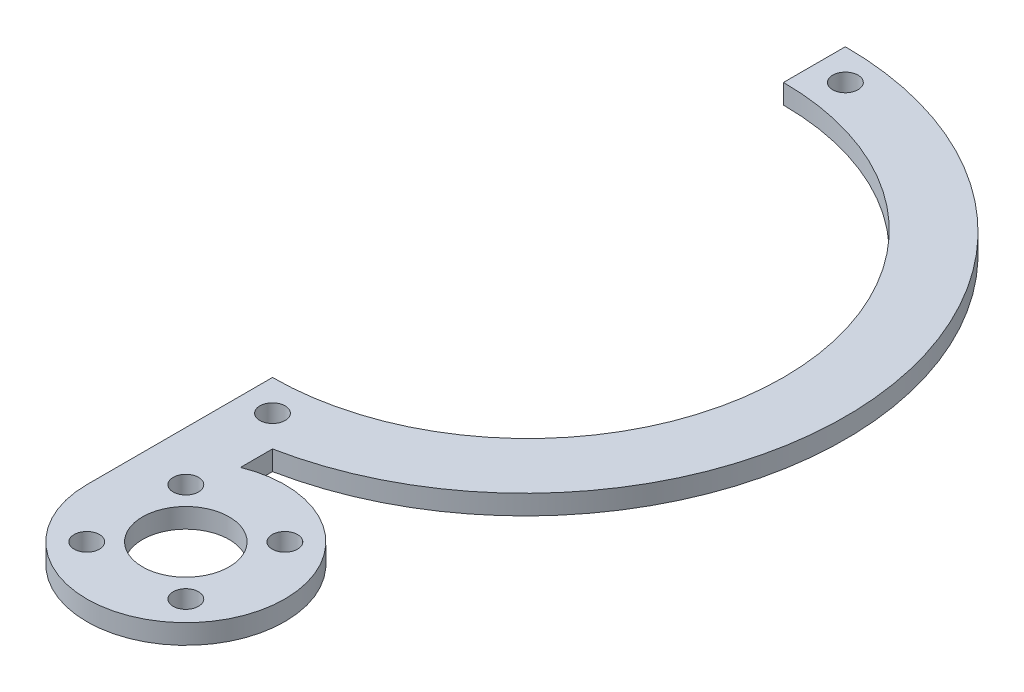
SolidWorks part; units mm, degrees
ref_plane "Front Plane" through (0, 0, 0) normal (0, 0, 1) x (1, 0, 0)
ref_plane "Top Plane" through (0, 0, 0) normal (0, 1, 0) x (1, 0, 0)
ref_plane "Right Plane" through (0, 0, 0) normal (1, 0, 0) x (0, 0, -1)
sketch "Sketch1" plane through (0, 0, 0) normal (0, 1, 0) x (1, 0, 0)
  line L0 (-16, 0) -> (-16, -50000) construction
  line L1 (8, -8) -> (-8, -8) construction
  line L2 (8, -8) -> (8, 8) construction
  line L3 (8, 8) -> (-8, 8) construction
  line L4 (-8, -8) -> (-8, 8) construction
  line L5 (8, -8) -> (-8, 8) construction
  line L6 (8, 8) -> (-8, -8) construction
  line L7 (-37.5308, 20) -> (49962.4692, 20) construction
  line L8 (0, 0) -> (50000, 0) construction
  line L10 (-16, 71.275) -> (49984, 71.275) construction
  line L11 (-16, 112.55) -> (49984, 112.55) construction
  line L12 (25.275, 61.275) -> (25.275, -49938.725) construction
  line L13 (-16, 122.55) -> (-16, 112.55)
  line L15 (-16, 30) -> (-16, 0)
  line L16 (-6, 19.4745) -> (-6, -49980.5255) construction
  line L17 (-6, 20) -> (-6, 14.8324)
  line L18 (-11, 20) -> (-11, 50020) construction
  line L19 (-11, 25) -> (-50011, 25) construction
  arc A0 (-16, 0) -> (16, 0) centre (0, 0) ccw
  arc A2 (-16, 112.55) -> (-16, 30) centre (-16, 71.275) cw
  arc A3 (-16, 122.55) -> (-6, 20) centre (-16, 70.7874) cw
  circle A4 centre (0, 0) radius 16 construction
  arc A5 (16, 0) -> (-6, 14.8324) centre (0, 0) ccw
  circle A6 centre (-8, 8) radius 2.05
  circle A7 centre (8, 8) radius 2.05
  circle A8 centre (8, -8) radius 2.05
  circle A9 centre (-8, -8) radius 2.05
  circle A10 centre (-11, 25) radius 2.05
  circle A11 centre (-11, 117.55) radius 2.05
  circle A12 centre (0, 0) radius 7
  point P1 (-16, 20)
  point P15 (-6, 20)
  point P25 (-16, 30)
  point P27 (-16, 122.55)
  dimension "D3" = 32
  dimension "D12" = 4.1
  dimension "D15" = 14
  dimension "D1" = 16
  dimension "D2" = 16
  dimension "D4" = 20
  dimension "D7" = 41.275
  dimension "D8" = 41.275
  dimension "D6" = 41.275
  dimension "D10" = 10
  dimension "D5" = 10
  dimension "D9" = 10
  dimension "D11" = 10
  dimension "D13" = 5
  dimension "D14" = 5
extrude "Boss-Extrude1" add sketch "Sketch1" along normal blind 3.175
equation "\"largestConeDiameter\"= 3.25in"
equation "\"D7@Sketch1\"=\"largestConeDiameter\"/2"
equation "\"D8@Sketch1\"=\"largestConeDiameter\"/2"
equation "\"D6@Sketch1\"=\"largestConeDiameter\"/2"
equation "\"thick\"= 3.175mm"
equation "\"sh\" = 4.1mm"
equation "\"D12@Sketch1\"=\"sh\""
equation "\"D1@Boss-Extrude1\"=\"thick\""
